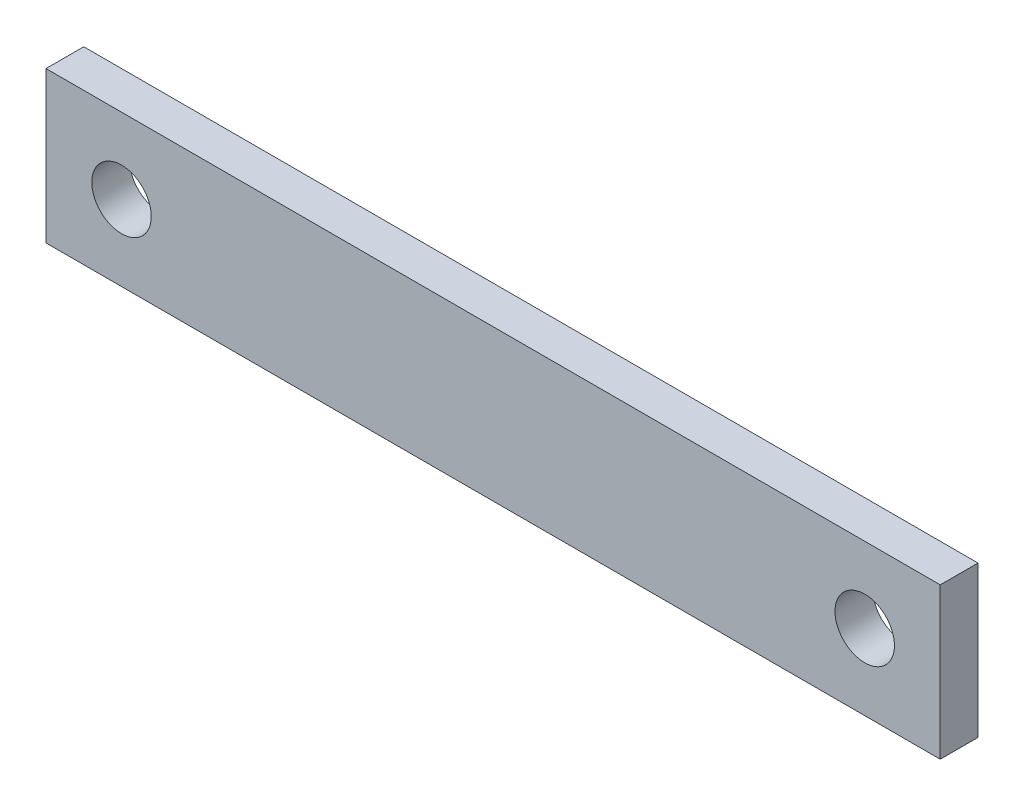
SolidWorks part; units mm, degrees
ref_plane "Front Plane" through (0, 0, 0) normal (0, 0, 1) x (1, 0, 0)
ref_plane "Top Plane" through (0, 0, 0) normal (0, 1, 0) x (1, 0, 0)
ref_plane "Right Plane" through (0, 0, 0) normal (1, 0, 0) x (0, 0, -1)
sketch "Sketch2" plane through (0, 0, 0) normal (0, 0, 1) x (1, 0, 0)
  line L0 (0, 12.7) -> (12.7, 12.7) construction
  line L1 (0, 0) -> (150.368, 0)
  line L2 (0, 0) -> (0, 25.4)
  line L3 (0, 25.4) -> (150.368, 25.4)
  line L4 (150.368, 0) -> (150.368, 25.4)
  line L5 (150.368, 12.7) -> (137.668, 12.7) construction
  circle A0 centre (137.668, 12.7) radius 5
  circle A1 centre (12.7, 12.7) radius 5
  dimension "D4" = 10
  dimension "D1" = 150.368
  dimension "D2" = 25.4
  dimension "D3" = 12.7
extrude "Boss-Extrude1" add sketch "Sketch2" against normal blind 6.35
